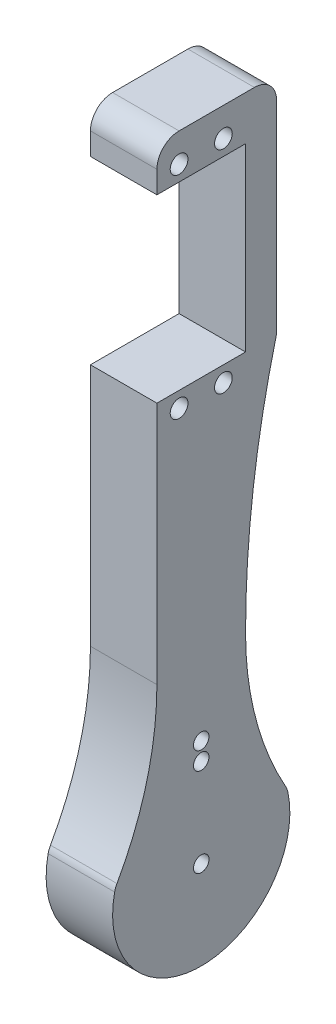
SolidWorks part; units mm, degrees
ref_plane "Front Plane" through (0, 0, 0) normal (1, 0, 0) x (0, 1, 0)
ref_plane "Top Plane" through (0, 0, 0) normal (0, 0, 1) x (0, 1, 0)
ref_plane "Right Plane" through (0, 0, 0) normal (0, 1, 0) x (-1, 0, 0)
sketch "Sketch1" plane through (0, 0, 0) normal (1, 0, 0) x (0, 1, 0)
  line L0 (0, 0) -> (105, 0) construction
  line L1 (95, 10) -> (95, -10) construction
  line L2 (95, -10) -> (135.7, -10) construction
  line L3 (135.7, -10) -> (135.7, 10) construction
  line L5 (95, 10) -> (40, 10)
  line L6 (40, 14.0198) -> (40, -15.1604) construction
  line L7 (95.6327, -17) -> (140.7, -17)
  line L8 (145.7, -12) -> (145.7, 5)
  line L9 (140.7, 10) -> (135.7, 10)
  line L10 (135.7, 10) -> (135.7, -10)
  line L11 (135.7, -10) -> (95, -10)
  line L12 (95, -10) -> (95, 10)
  line L13 (115.35, -10) -> (115.35, 15.9871) construction
  arc A0 (4.2445, 19.5444) -> (4.2445, -19.5444) centre (0, 0) ccw
  arc A1 (40, 10) -> (5.6378, 19.0144) centre (40, 80) cw
  arc A2 (40, -10) -> (5.6378, -19.0144) centre (40, -80) ccw
  arc A3 (40, -10) -> (94.3941, -16.8441) centre (40, -229.5714) cw
  arc A4 (145.7, 5) -> (140.7, 10) centre (140.7, 5) ccw
  arc A5 (145.7, -12) -> (140.7, -17) centre (140.7, -12) cw
  arc A6 (95.6327, -17) -> (94.3941, -16.8441) centre (95.6327, -12) cw
  arc A7 (5.6378, -19.0144) -> (4.2445, -19.5444) centre (3.1834, -14.6583) cw
  arc A8 (5.6378, 19.0144) -> (4.2445, 19.5444) centre (3.1834, 14.6583) ccw
  circle A9 centre (139.2, -5) radius 2
  circle A10 centre (139.2, 5) radius 2
  circle A11 centre (91.5, -5) radius 2
  circle A12 centre (91.5, 5) radius 2
  point P21 (145.7, 10)
  point P26 (95, -17)
  point P29 (5.0419, -19.354)
  point P32 (5.0419, 19.354)
  dimension "D1" = 40
  dimension "D8" = 70
  dimension "D11" = 5
  dimension "D13" = 4
  dimension "D2" = 105
  dimension "D3" = 40.7
  dimension "D4" = 20
  dimension "D5" = 10
  dimension "D6" = 10
  dimension "D7" = 40
  dimension "D9" = 7
  dimension "D10" = 10
  dimension "D12" = 5
  dimension "D14" = 3.5
  dimension "D15" = 10
extrude "Boss-Extrude1" add sketch "Sketch1" along normal blind 15
sketch "Sketch2" plane through (0, 0, 0) normal (-1, 0, 0) x (0, -1, 0)
  line L0 (-24.3305, -3.5) -> (-12, -3.5)
  line L1 (-24.3305, 3.5) -> (-12, 3.5)
  line L2 (-12, -3.5) -> (-12, 3.5) construction
  arc A0 (-5.1536, -5.4489) -> (-5.1536, 5.4489) centre (0, 0) ccw
  arc A1 (-12, -3.5) -> (-5.1536, -5.4489) centre (-12, -16.5) cw
  arc A2 (-12, 3.5) -> (-5.1536, 5.4489) centre (-12, 16.5) ccw
  arc A3 (-24.3305, 3.5) -> (-24.3305, -3.5) centre (-24.3305, 0) ccw
  dimension "D2" = 15
  dimension "D4" = 13
  dimension "D1" = 12
  dimension "D3" = 24.3305
extrude "Cut-Extrude1" cut sketch "Sketch2" against normal blind 3.86
sketch "Sketch3" plane through (3.86, 0, 0) normal (-1, 0, 0) x (0, -1, 0)
  line L0 (0, 0) -> (-26.8985, 0) construction
  circle A0 centre (0, 0) radius 1.75
  circle A1 centre (-20, 0) radius 1.75
  circle A2 centre (-24, 0) radius 1.75
  dimension "D1" = 3.5
  dimension "D2" = 20
  dimension "D3" = 24
extrude "Cut-Extrude2" cut sketch "Sketch3" against normal through all
